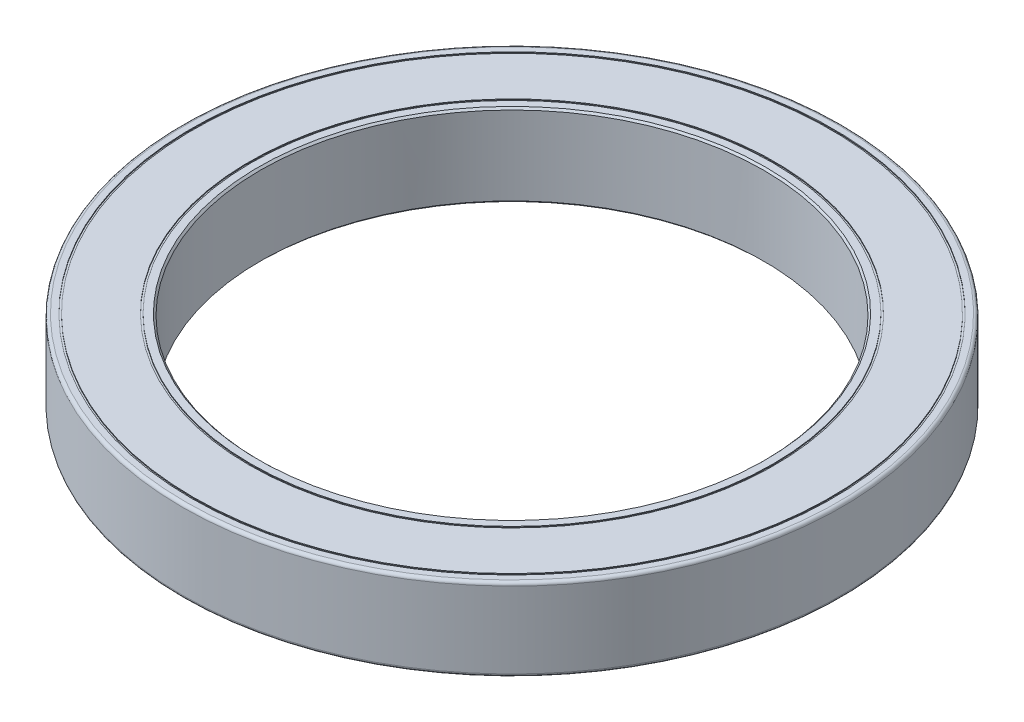
SolidWorks part; units mm, degrees
ref_plane "Front Plane" through (0, 0, 0) normal (0, 0, 1) x (1, 0, 0)
ref_plane "Top Plane" through (0, 0, 0) normal (0, 1, 0) x (1, 0, 0)
ref_plane "Right Plane" through (0, 0, 0) normal (1, 0, 0) x (0, 0, -1)
sketch "Sketch1" plane through (0, 0, 0) normal (0, 0, 1) x (1, 0, 0)
  line L0 (0, 0) -> (27.5, 0) construction
  line L1 (36, 0) -> (36, 9)
  line L3 (0, 4.5) -> (0, 0) construction
  line L4 (27.5, 0) -> (27.5, 9)
  line L5 (27.5, 0) -> (28.5, 0)
  line L6 (28.5, 0) -> (28.5, 0.1)
  line L7 (28.5, 0.1) -> (28.7, 0.1)
  line L8 (28.7, 0.1) -> (28.7, 0)
  line L9 (28.7, 0) -> (34.8, 0)
  line L10 (31.75, 0) -> (31.75, 4.5) construction
  line L11 (36, 4.5) -> (27.5, 4.5) construction
  line L12 (27.5, 4.5) -> (0, 4.5) construction
  line L13 (34.8, 0.1) -> (34.8, 0)
  line L14 (35, 0.1) -> (34.8, 0.1)
  line L15 (35, 0) -> (35, 0.1)
  line L16 (36, 0) -> (35, 0)
  line L17 (36, 9) -> (35, 9)
  line L18 (35, 9) -> (35, 8.9)
  line L19 (35, 8.9) -> (34.8, 8.9)
  line L20 (34.8, 8.9) -> (34.8, 9)
  line L21 (28.7, 9) -> (34.8, 9)
  line L22 (28.7, 8.9) -> (28.7, 9)
  line L23 (28.5, 8.9) -> (28.7, 8.9)
  line L24 (28.5, 9) -> (28.5, 8.9)
  line L25 (27.5, 9) -> (28.5, 9)
  dimension "D1" = 36
  dimension "D2" = 27.5
  dimension "D4" = 1
  dimension "D5" = 0.2
  dimension "D6" = 0.1
  dimension "D3" = 9
revolve "Revolve1" add sketch "Sketch1" angle 360 about L3
fillet "Fillet2" radius 0.344 2 edges at (0, 0, 36) (0, 9, 36)
chamfer "Chamfer2" distance 0.2 angle 45 2 edges at (0, 0, 27.5) (0, 9, 27.5)
equation "\"Ratio\"= 15"
equation "\"Hull Diameter\"= 92"
equation "\"Fixed Ring Diameter\"= 76"
equation "\"Fixed Pin Diameter\"= 6"
equation "\"Output Ring Diameter\"= 40"
equation "\"Output Pin Diameter\"= 6"
equation "\"Disk Bearing Inner Diameter\"= 9"
equation "\"Disk Bearing Outer Diameter\"= 17"
equation "\"Disk Bearing Height\"= 5"
equation "\"Shaft Bearing Inner Diameter\"= 15"
equation "\"Shaft Bearing Outer Diameter\"= 21"
equation "\"Shaft Bearing Height\"= 4"
equation "\"Eccentricity\"= 1.5"
equation "\"Disk Height\"= 8"
equation "\"Disk Spacing\"= 5"
equation "\"Hull Height\"= 40"
equation "\"Shaft End Bearing Inner Diameter\"= 12"
equation "\"Shaft End Bearing Outer Diameter\"= 18"
equation "\"Shaft End Bearing Height\"= 4"
equation "\"Output Bearing Inner Diameter\"= 55"
equation "\"Output Bearing Outer Diameter\"= 72"
equation "\"Outer Bearing Height\"= 9"
equation "\"D3@Sketch1\"=\"Outer Bearing Height\""
equation "\"D2@Sketch1\"=\"Output Bearing Inner Diameter\"/2"
equation "\"D1@Sketch1\"=\"Output Bearing Outer Diameter\"/2"
